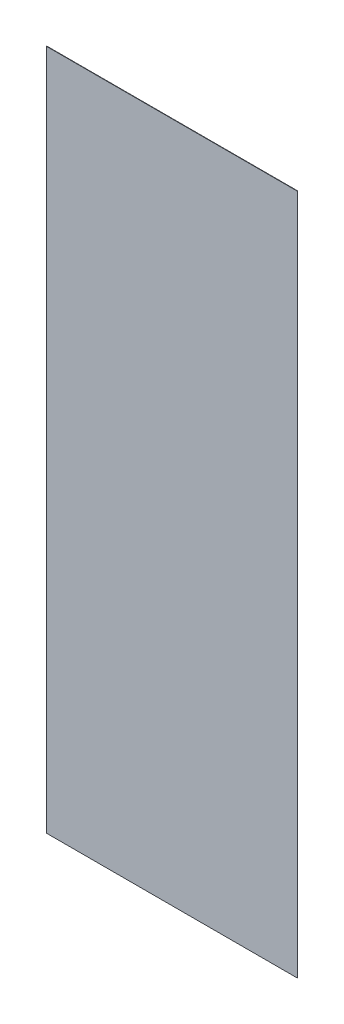
SolidWorks part; units mm, degrees
ref_plane "Front Plane" through (0, 0, 0) normal (0, 0, 1) x (1, 0, 0)
ref_plane "Top Plane" through (0, 0, 0) normal (0, 1, 0) x (1, 0, 0)
ref_plane "Right Plane" through (0, 0, 0) normal (1, 0, 0) x (0, 0, -1)
other "Configuration Table"
sketch "Sketch1" plane through (0, 0, 0) normal (0, 0, 1) x (1, 0, 0)
  line L1 (31.5, 120) -> (668.5, 120)
  line L2 (31.5, 120) -> (31.5, 1850)
  line L3 (31.5, 1850) -> (668.5, 1850)
  line L4 (668.5, 120) -> (668.5, 1850)
extrude "OVEN_arka_kanal_bolme_saci_1" add sketch "Sketch1" against normal blind 1 from offset 580 separate body
